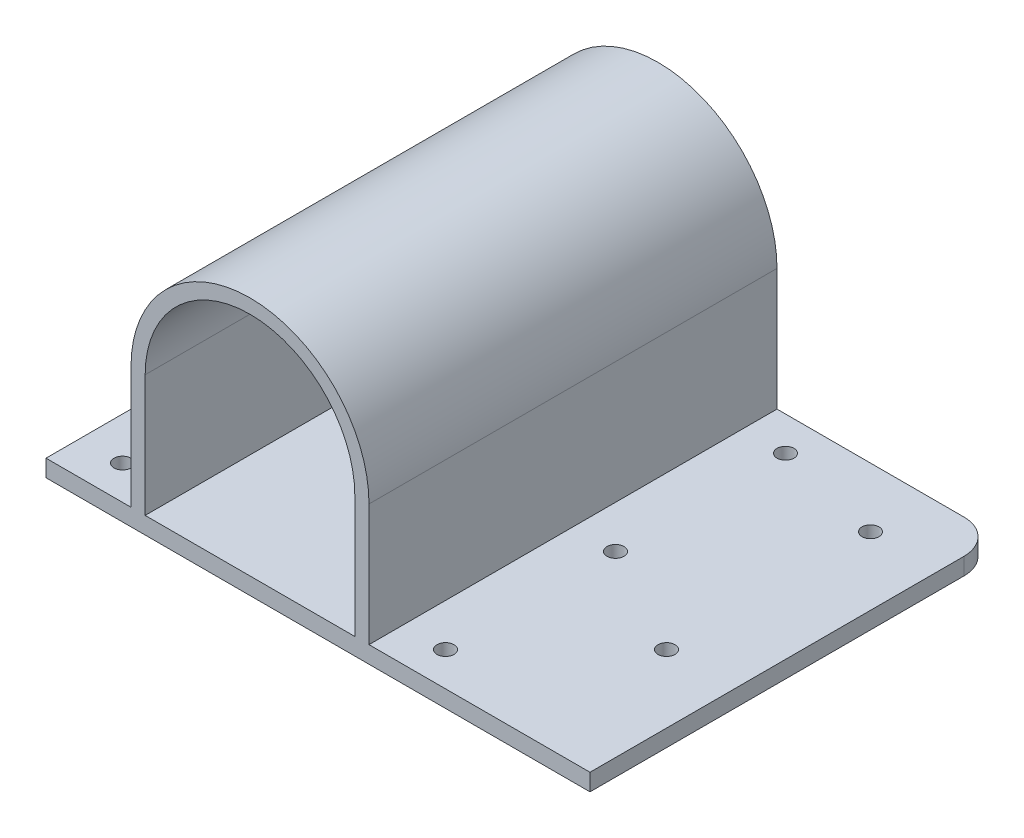
SolidWorks part; units mm, degrees
ref_plane "Front Plane" through (0, 0, 0) normal (0, 0, 1) x (1, 0, 0)
ref_plane "Top Plane" through (0, 0, 0) normal (0, 1, 0) x (1, 0, 0)
ref_plane "Right Plane" through (0, 0, 0) normal (1, 0, 0) x (0, 0, -1)
sketch "Sketch1" plane through (0, 0, 0) normal (0, 0, 1) x (1, 0, 0)
  line L0 (-21, 0) -> (-21, -21.5)
  line L1 (-21, -21.5) -> (-36, -21.5)
  line L2 (-36, -21.5) -> (-36, -24.5)
  line L3 (-36, -24.5) -> (36, -24.5)
  line L4 (36, -24.5) -> (36, -21.5)
  line L5 (36, -21.5) -> (21, -21.5)
  line L6 (21, -21.5) -> (21, 0)
  line L7 (0, 0) -> (7, 0) construction
  line L8 (0, 0) -> (0, 15.5) construction
  line L9 (-21, -21.5) -> (21, -21.5) construction
  arc A0 (21, 0) -> (-21, 0) centre (0, 0) ccw
  circle A2 centre (0, 15.5) radius 1.65
  circle A3 centre (13.4234, 7.75) radius 1.65
  circle A4 centre (13.4234, -7.75) radius 1.65
  circle A5 centre (0, -15.5) radius 1.65
  circle A6 centre (-13.4234, -7.75) radius 1.65
  circle A7 centre (-13.4234, 7.75) radius 1.65
  circle A8 centre (0, 0) radius 18.5 construction
  circle A9 centre (7, 0) radius 6.15
  point P15 (0, -24.5)
  point P27 (0, 0)
  point P28 (0, -18.5)
  dimension "D1" = 42
  dimension "D6" = 0
  dimension "D7" = 3.3
  dimension "D10" = 37
  dimension "D11" = 2.5
  dimension "D12" = 90
  dimension "D3" = 12.3
  dimension "D2" = 7
  dimension "D4" = 72
  dimension "D5" = 3
  dimension "D8" = 15.5
  dimension "D13" = 3
  dimension "D9" = 6
extrude "Boss-Extrude1" add sketch "Sketch1" along normal blind 72
sketch "Sketch2" plane through (0, 0, 72) normal (0, 0, 1) x (1, 0, 0)
  line L0 (-18.5, 0) -> (-18.5, -21.5)
  line L2 (-18.5, -21.5) -> (18.5, -21.5)
  line L3 (18.5, -21.5) -> (18.5, 0)
  line L4 (-21, -21.5) -> (-36, -21.5) construction
  arc A0 (18.5, 0) -> (-18.5, 0) centre (0, 0) ccw
  arc A1 (-18.5, 0) -> (18.5, 0) centre (0, 0) ccw construction
  dimension "D1" = 37
extrude "Cut-Extrude1" cut sketch "Sketch2" against normal blind 57
sketch "Sketch3" plane through (0, -21.5, 0) normal (0, 1, 0) x (1, 0, 0)
  line L0 (0, 0) -> (0, -72) construction
  line L1 (-21, -72) -> (21, -72) construction
  line L2 (-28.5, 0) -> (-28.5, -72) construction
  line L3 (-21, 0) -> (-36, 0) construction
  line L4 (-21, -72) -> (-36, -72) construction
  circle A0 centre (-28.5, -36) radius 1.5
  circle A1 centre (-28.5, -6) radius 1.5
  circle A2 centre (-28.5, -66) radius 1.5
  circle A3 centre (28.5, -66) radius 1.5
  circle A4 centre (28.5, -6) radius 1.5
  circle A5 centre (28.5, -36) radius 1.5
  dimension "D1" = 30
  dimension "D2" = 30
  dimension "D3" = 3
extrude "Cut-Extrude2" cut sketch "Sketch3" against normal through all
sketch "Sketch4" plane through (0, -21.5, 0) normal (0, 1, 0) x (1, 0, 0)
  line L0 (36, -72) -> (36, 0) construction
  line L1 (36, -72) -> (36, 0)
  line L2 (36, 0) -> (60, 0)
  line L3 (60, 0) -> (60, -72)
  line L4 (60, -72) -> (36, -72)
  line L5 (48, -72) -> (48, 0) construction
  circle A0 centre (48, -10.5) radius 1.5
  circle A1 centre (48, -46.5) radius 1.5
  point P11 (0, 0)
  dimension "D3" = 36
  dimension "D4" = 3
  dimension "D5" = 10.5
  dimension "D1" = 24
  dimension "D2" = 12
extrude "Boss-Extrude2" add sketch "Sketch4" against normal blind 3
fillet "Fillet1" radius 6 1 edges at (60, -23, 0)
